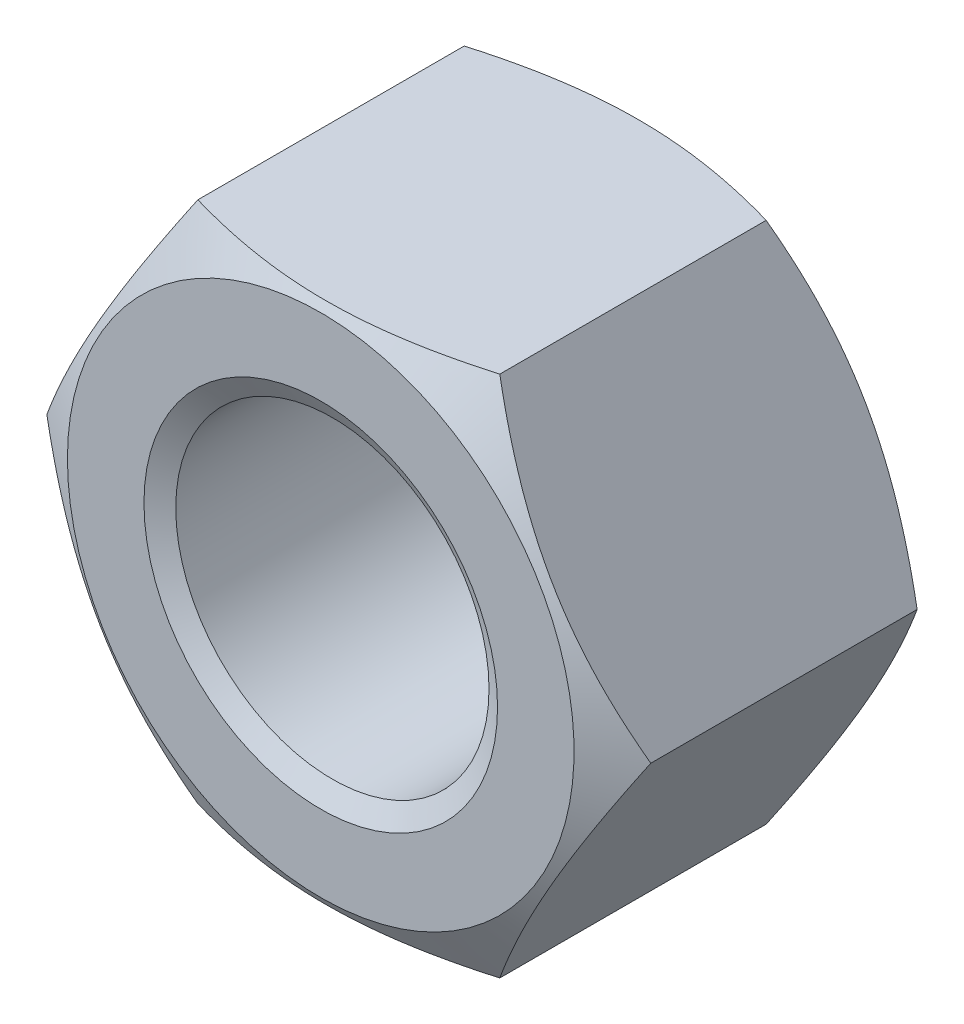
SolidWorks part; units mm, degrees
ref_plane "Front" through (0, 0, 0) normal (0, 0, 1) x (1, 0, 0)
ref_plane "Top" through (0, 0, 0) normal (0, 1, 0) x (1, 0, 0)
ref_plane "Right" through (0, 0, 0) normal (1, 0, 0) x (0, 0, -1)
sketch "Sketch1" plane through (0, 0, 0) normal (0, 0, 1) x (1, 0, 0)
  line L1 (6.9282, -12) -> (13.8564, 0)
  line L2 (13.8564, 0) -> (6.9282, 12)
  line L3 (6.9282, 12) -> (-6.9282, 12)
  line L4 (-6.9282, 12) -> (-13.8564, 0)
  line L5 (-13.8564, 0) -> (-6.9282, -12)
  line L6 (-6.9282, -12) -> (6.9282, -12)
  circle A0 centre (0, 0) radius 12 construction
  circle A1 centre (0, 0) radius 7.188
  dimension "D" = 14.376
  dimension "s" = 24
extrude "BaseNut" add sketch "Sketch1" against normal blind 14.8
cosmetic thread "ThreadCosmetic1" [suppressed] parameters "D"=16
sketch "Sketch2" plane through (0, 0, 0) normal (0, 1, 0) x (1, 0, 0)
  line L0 (-13.8564, 14.8) -> (-11.625, 14.8)
  line L2 (-11.625, 14.8) -> (-13.8564, 13.5117)
  line L3 (-13.8564, 13.5117) -> (-13.8564, 14.8)
  line L4 (0, 9.8171) -> (0, -9.8171) construction
  line L6 (-9.7712, 7.4) -> (9.8853, 7.4) construction
  line L7 (-13.8564, 1.2883) -> (-13.8564, 0)
  line L8 (-11.625, 0) -> (-13.8564, 1.2883)
  line L9 (-13.8564, 0) -> (-11.625, 0)
  dimension "D1" = 30
  dimension "dw" = 23.25
  dimension "D2" = 7.4
revolve "Double-Chamfer" cut sketch "Sketch2" angle 360 about L4
chamfer "EndChamfer" distance 0.925 angle 30 2 edges at (7.188, 0, -14.8) (7.188, 0, 0)
sketch "Sketch3" plane through (0, 0, 0) normal (0, 1, 0) x (1, 0, 0)
  line L0 (-7.8912, 13.875) -> (-7.188, 13.469)
  line L1 (-7.188, 13.469) -> (-6.376, 13.469)
  line L2 (-6.376, 13.469) -> (-6.376, 14.281)
  line L3 (-6.376, 14.281) -> (-7.188, 14.281)
  line L4 (-7.188, 14.281) -> (-7.8912, 13.875)
  line L5 (0, 5.5171) -> (0, 12.3415) construction
  dimension "D1" = 0.812
  dimension "D2" = 14.376
revolve "Cut-Revolve10" [suppressed] cut sketch "Sketch3" angle 360 about L5
pattern_linear "LPattern10" [suppressed] count 14 spacing 0.9744 along (0, 0, -1)
equation "\"dw@Sketch2\" = \"s@Sketch1\"-0.75"
equation "\"D1@EndChamfer\" = \"m@BaseNut\" / 16"
equation "\"D2@Sketch2\" = \"m@BaseNut\" / 2"
equation "\"D2@Sketch3\"=\"D@Sketch1\""
equation "\"D1@Sketch3\" =  ( \"D@ThreadCosmetic1\" - \"D@Sketch1\" )  / 2"
equation "\"D3@LPattern10\"=\"D1@Sketch3\" * 1.2"
equation "\"D1@LPattern10\" = \"m@BaseNut\" / \"D3@LPattern10\"-1"
